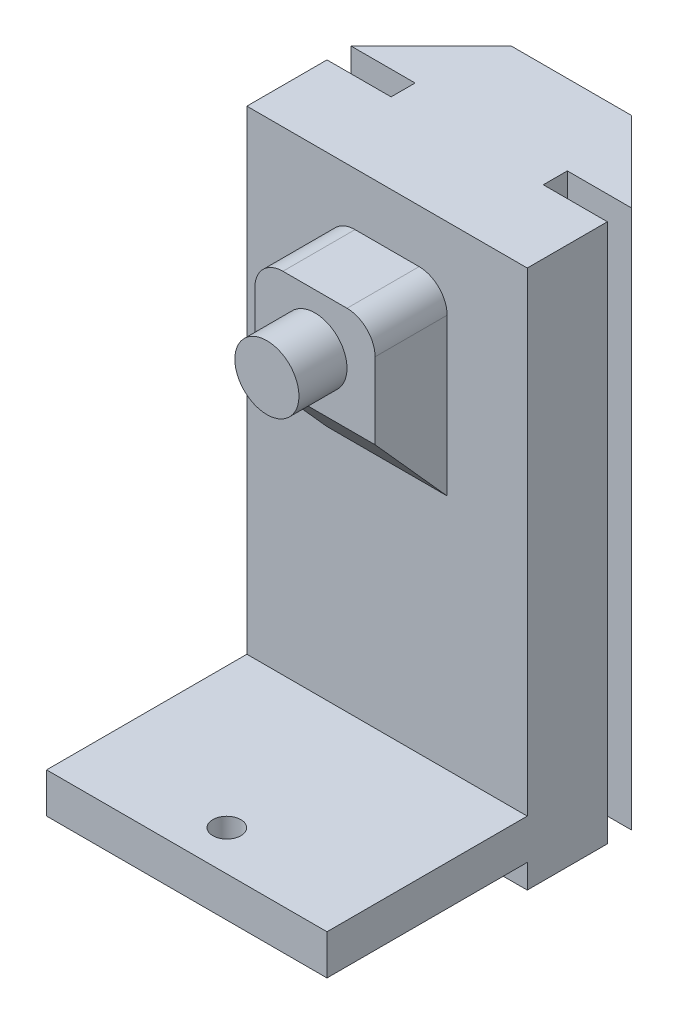
SolidWorks part; units mm, degrees
ref_plane "Alzado" through (0, 0, 0) normal (0, 0, 1) x (1, 0, 0)
ref_plane "Planta" through (0, 0, 0) normal (0, 1, 0) x (1, 0, 0)
ref_plane "Vista lateral" through (0, 0, 0) normal (1, 0, 0) x (0, 0, -1)
sketch "Croquis2" plane through (0, 0, 0) normal (0, 1, 0) x (1, 0, 0)
  line L7 (0, -27.1211) -> (0, -7.24) construction
  line L8 (-17.5, -27.1211) -> (17.5, -27.1211)
  line L9 (-17.5, -27.1211) -> (-17.5, -17.1211)
  line L11 (17.5, -27.1211) -> (17.5, -17.1211)
  line L12 (-17.5, -14.1211) -> (-7.5, -4.1211)
  line L14 (-17.5, -17.1211) -> (-9.5, -17.1211)
  line L16 (-17.5, -14.1211) -> (-9.5, -14.1211)
  line L17 (-9.5, -17.1211) -> (-9.5, -14.1211)
  line L18 (17.5, -14.1211) -> (7.5, -4.1211)
  line L19 (-7.5, -4.1211) -> (7.5, -4.1211)
  line L20 (17.5, -17.1211) -> (9.5, -17.1211)
  line L22 (17.5, -14.1211) -> (9.5, -14.1211)
  line L23 (9.5, -17.1211) -> (9.5, -14.1211)
  point P13 (17.5, -7.24)
  dimension "D1" = 8
  dimension "D3" = 10
  dimension "D5" = 3
  dimension "D6" = 10
  dimension "D7" = 3
  dimension "D8" = 45
  dimension "D9" = 45
extrude "Saliente-Extruir1" add sketch "Croquis2" along normal blind 67.25
sketch "Croquis7" plane through (0, 0, 27.1211) normal (0, 0, 1) x (1, 0, 0)
  line L0 (-17.5, 0) -> (17.5, 0) construction
  circle A0 centre (0, 54.15) radius 4
  dimension "D1" = 54.15
  dimension "D2" = 8
extrude "Saliente-Extruir2" add sketch "Croquis7" along normal blind 15
sketch "Croquis8" plane through (0, 0, 0) normal (1, 0, 0) x (0, 0, -1)
  line L0 (-36.1211, 47.65) -> (-30.5234, 47.65)
  line L1 (-30.5234, 47.65) -> (-27.1211, 47.65)
  line L8 (-42.1211, 50.15) -> (-36.1211, 50.15) construction
  line L15 (-36.1211, 47.65) -> (-27.1211, 37.61)
  line L16 (-27.1211, 47.65) -> (-27.1211, 37.61)
  dimension "D1" = 2.5
extrude "Saliente-Extruir9" add sketch "Croquis8" along normal mid plane 15 separate body
sketch "Croquis15" plane through (0, 0, 27.1211) normal (0, 0, 1) x (1, 0, 0)
  line L0 (7.5, 47.65) -> (7.5, 37.61) construction
  line L1 (-7.5, 47.65) -> (7.5, 47.65)
  line L2 (-7.5, 47.65) -> (-7.5, 57.15)
  line L3 (-4, 60.65) -> (4, 60.65)
  line L4 (7.5, 47.65) -> (7.5, 57.15)
  line L5 (-7.5, 47.65) -> (7.5, 60.65) construction
  line L6 (-7.5, 60.65) -> (7.5, 47.65) construction
  line L7 (0, 58.15) -> (0, 60.65) construction
  circle A0 centre (0, 54.15) radius 4 construction
  circle A1 centre (0, 54.15) radius 4
  arc A2 (-7.5, 57.15) -> (-4, 60.65) centre (-4, 57.15) cw
  arc A3 (4, 60.65) -> (7.5, 57.15) centre (4, 57.15) cw
  point P0 (0, 54.15)
  dimension "D2" = 3.5
  dimension "D1" = 2.5
extrude "Saliente-Extruir15" add sketch "Croquis15" along normal blind 9
ref_plane "Plano1" through (7.5, 37.61, 27.1211) normal (-1, 0, 0) x (0, 0, 1)
sketch "Croquis17" plane through (0, 0, 0) normal (1, 0, 0) x (0, 0, -1)
  line L0 (-27.1211, 67.25) -> (-27.1211, 0) construction
  line L4 (-52.1211, 3) -> (-52.1211, 8)
  line L5 (-27.1211, 5.5) -> (-52.1211, 8) construction
  line L6 (-27.1211, 5.5) -> (-52.1211, 3) construction
  line L8 (-52.1211, 8) -> (-27.1211, 8)
  line L9 (-27.1211, 8) -> (-27.1211, 3)
  line L10 (-27.1211, 3) -> (-52.1211, 3)
  point P0 (-27.1211, 5.5)
  dimension "D2" = 5
  dimension "D3" = 25
extrude "Saliente-Extruir16" add sketch "Croquis17" along normal mid plane 35
sketch "Croquis18" plane through (0, 8, 0) normal (0, 1, 0) x (1, 0, 0)
  line L0 (17.5, -52.1211) -> (-17.5, -52.1211) construction
  circle A0 centre (0, -47.1211) radius 1.75
  dimension "D1" = 3.5
  dimension "D2" = 5
extrude "Cortar-Extruir3" cut sketch "Croquis18" against normal mid plane 15
